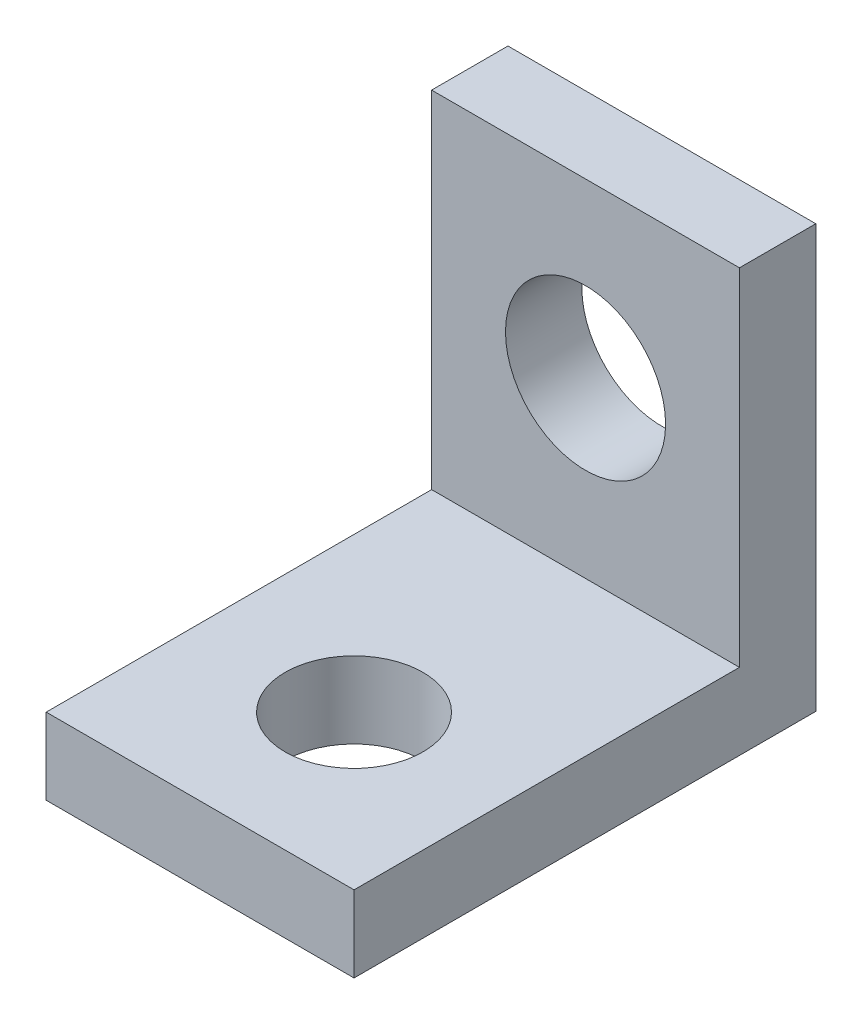
SolidWorks part; units mm, degrees
ref_plane "Front Plane" through (0, 0, 0) normal (0, 0, 1) x (1, 0, 0)
ref_plane "Top Plane" through (0, 0, 0) normal (0, 1, 0) x (1, 0, 0)
ref_plane "Right Plane" through (0, 0, 0) normal (1, 0, 0) x (0, 0, -1)
sketch "Sketch1" plane through (0, 0, 0) normal (1, 0, 0) x (0, 0, -1)
  line L0 (0, 0) -> (0, 8.7122)
  line L1 (0, 8.7122) -> (-1.5748, 8.7122)
  line L2 (-1.5748, 8.7122) -> (-1.5748, 1.5748)
  line L3 (-1.5748, 1.5748) -> (-9.525, 1.5748)
  line L4 (-9.525, 1.5748) -> (-9.525, 0)
  line L5 (-9.525, 0) -> (0, 0)
  dimension "D1" = 8.7122
  dimension "D2" = 9.525
  dimension "D3" = 1.5748
  dimension "D4" = 1.5748
extrude "Boss-Extrude1" add sketch "Sketch1" against normal blind 6.35
sketch "Sketch2" plane through (0, 0, 1.5748) normal (0, 0, 1) x (1, 0, 0)
  line L1 (-6.35, 0) -> (0, 0) construction
  circle A0 centre (-3.175, 5.1562) radius 1.651
  point P4 (-3.175, 0)
  dimension "D2" = 3.302
  dimension "D1" = 5.1562
extrude "Cut-Extrude1" cut sketch "Sketch2" against normal up to next
sketch "Sketch3" plane through (0, 1.5748, 0) normal (0, 1, 0) x (1, 0, 0)
  line L1 (-6.35, 0) -> (0, 0) construction
  circle A0 centre (-3.175, -6.35) radius 1.4224
  point P3 (-3.175, 0)
  dimension "D2" = 2.8448
  dimension "D1" = 6.35
extrude "Cut-Extrude2" cut sketch "Sketch3" against normal up to next
